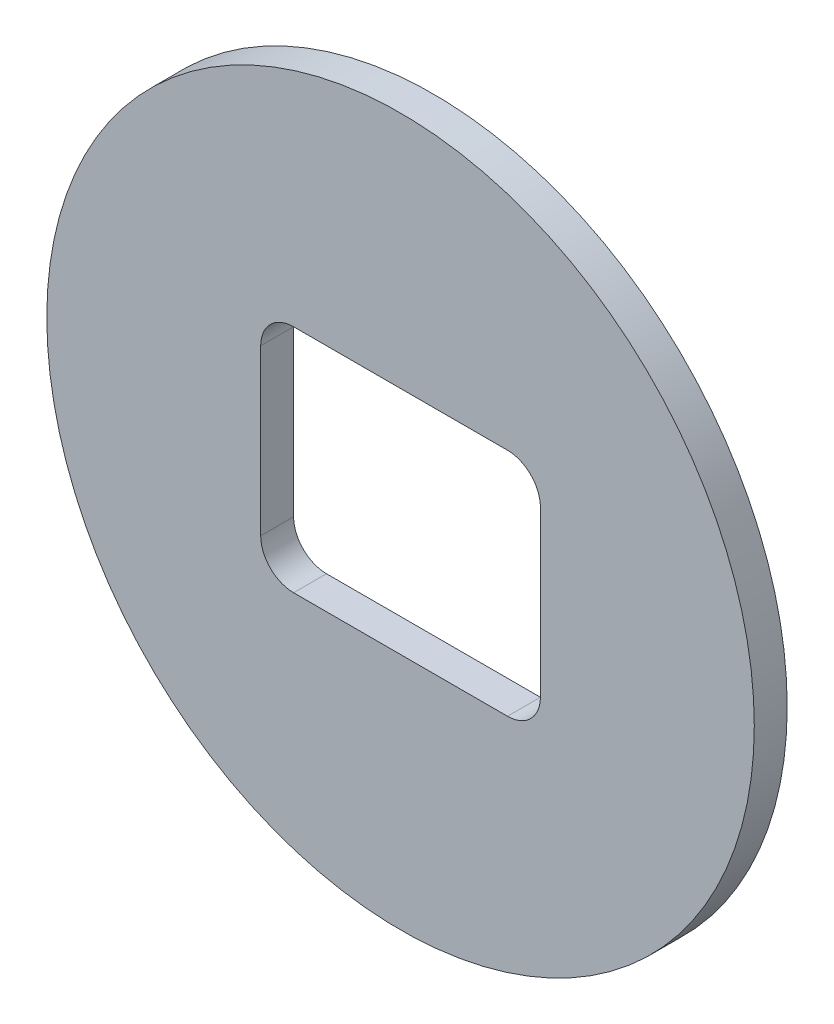
SolidWorks part; units mm, degrees
material "Acrylic (Medium-high impact)"
ref_plane "Front Plane" through (0, 0, 0) normal (0, 0, 1) x (1, 0, 0)
ref_plane "Top Plane" through (0, 0, 0) normal (0, 1, 0) x (1, 0, 0)
ref_plane "Right Plane" through (0, 0, 0) normal (1, 0, 0) x (0, 0, -1)
sketch "Sketch1" plane through (0, 0, 0) normal (0, 0, 1) x (1, 0, 0)
  line L1 (-8.5, -7) -> (8.5, -7)
  line L2 (-8.5, -7) -> (-8.5, 7)
  line L3 (-8.5, 7) -> (8.5, 7)
  line L4 (8.5, -7) -> (8.5, 7)
  line L5 (-8.5, -7) -> (8.5, 7) construction
  line L6 (-8.5, 7) -> (8.5, -7) construction
  circle A0 centre (0, 0) radius 21.5
  dimension "D1" = 43
  dimension "D2" = 14
  dimension "D3" = 17
extrude "Boss-Extrude2" add sketch "Sketch1" along normal blind 2
fillet "Fillet1" radius 2 4 edges at (-8.5, -7, 1) (8.5, -7, 1) (8.5, 7, 1) (-8.5, 7, 1)
